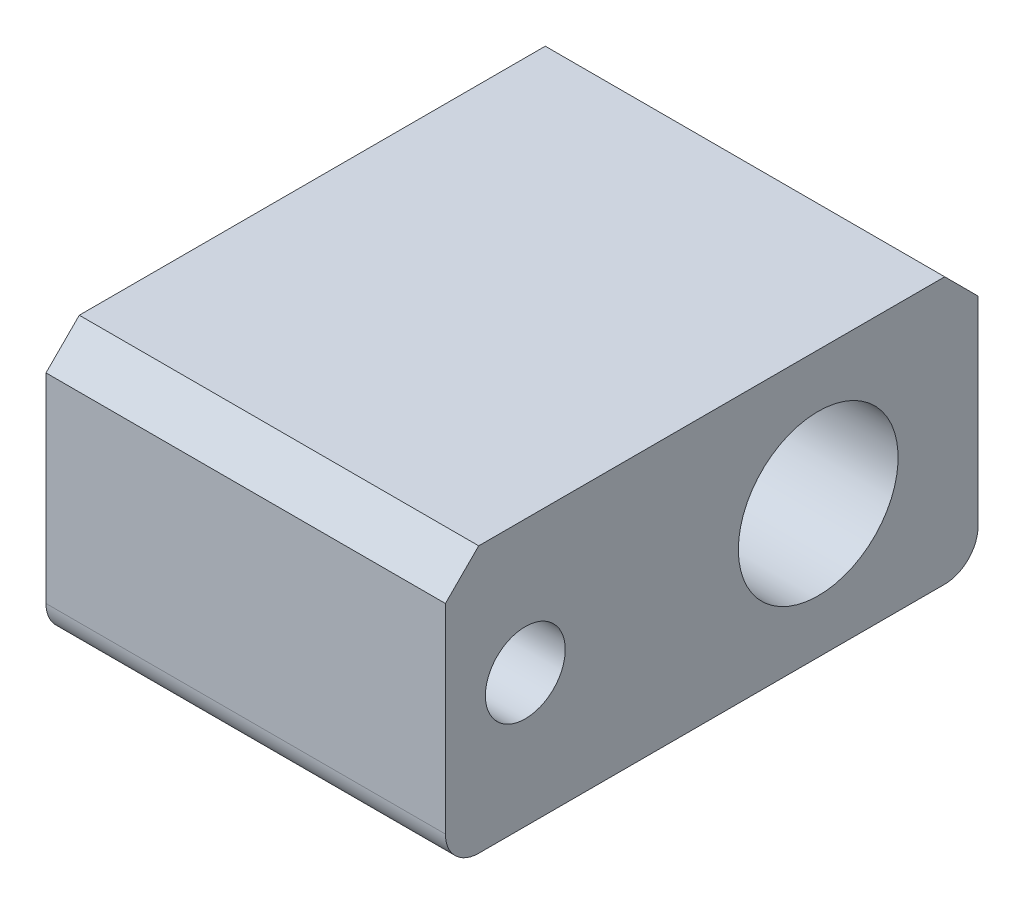
SolidWorks part; units mm, degrees
ref_plane "Front Plane" through (0, 0, 0) normal (1, 0, 0) x (0, 1, 0)
ref_plane "Top Plane" through (0, 0, 0) normal (0, 0, 1) x (0, 1, 0)
ref_plane "Right Plane" through (0, 0, 0) normal (0, 1, 0) x (-1, 0, 0)
sketch "Sketch1" plane through (0, 0, 0) normal (1, 0, 0) x (0, 1, 0)
  line L0 (0, -55) -> (0, 55) construction
  line L1 (25.4, -50.8) -> (-25.4, -50.8)
  line L2 (25.4, -50.8) -> (25.4, 50.8)
  line L3 (25.4, 50.8) -> (-25.4, 50.8)
  line L4 (-25.4, -50.8) -> (-25.4, 50.8)
  line L5 (25.4, -50.8) -> (-25.4, 50.8) construction
  line L6 (25.4, 50.8) -> (-25.4, -50.8) construction
  circle A0 centre (0, -20.32) radius 15.24
  circle A1 centre (0, 35.56) radius 7.62
  point P0 (0, 0)
  dimension "D3" = 30.48
  dimension "D5" = 15.24
  dimension "D1" = 50.8
  dimension "D2" = 101.6
  dimension "D4" = 30.48
  dimension "D6" = 15.24
extrude "Boss-Extrude1" add sketch "Sketch1" along normal blind 76.2
fillet "Fillet1" radius 6.35 2 edges at (38.1, -25.4, -50.8) (38.1, -25.4, 50.8)
chamfer "Chamfer1" distance 6.35 angle 45 2 edges at (38.1, 25.4, -50.8) (38.1, 25.4, 50.8)
